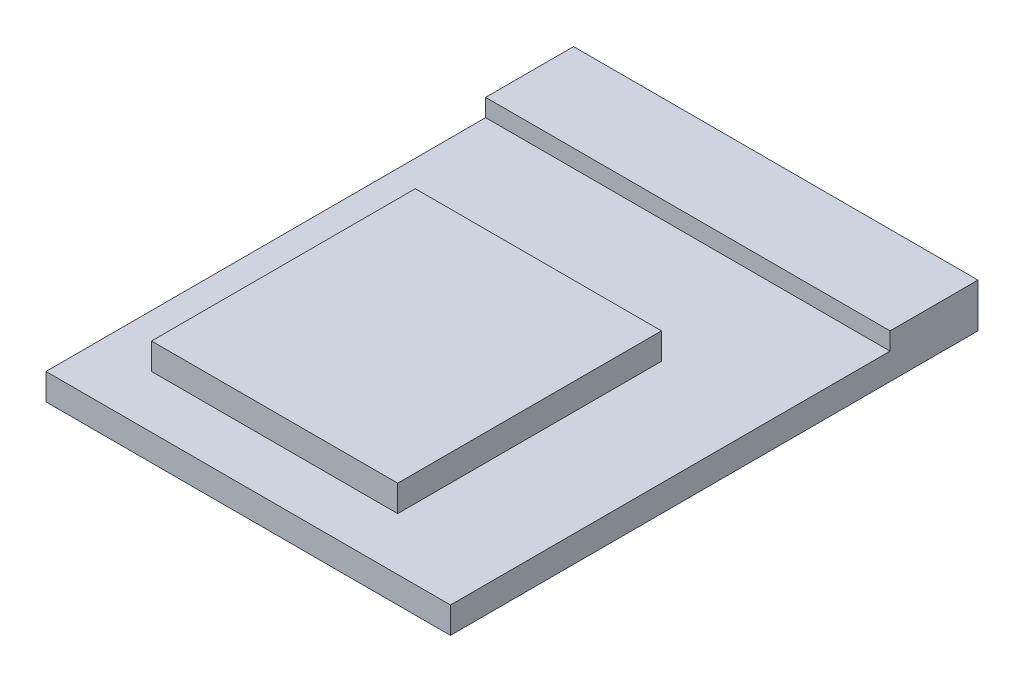
SolidWorks part; units mm, degrees
other "Исправление1"
sketch "Эскиз4"
other "Исправление2"
sketch "Эскиз5"
other "Исправление3"
sketch "Эскиз6" plane through (23, 3, 30) normal (0.5061, 0.739, 0.4446) x (0.6964, -0.0461, -0.7162)
ref_plane "Спереди" through (0, 0, 0) normal (0, 0, 1) x (1, 0, 0)
ref_plane "Сверху" through (0, 0, 0) normal (0, 1, 0) x (1, 0, 0)
ref_plane "Справа" through (0, 0, 0) normal (1, 0, 0) x (0, 0, -1)
other "Configuration Table"
sketch "Эскиз1" plane through (0, 0, 0) normal (0, 1, 0) x (1, 0, 0)
  line L1 (0, 0) -> (23, 0)
  line L2 (0, 0) -> (0, -30)
  line L3 (0, -30) -> (23, -30)
  line L4 (23, 0) -> (23, -30)
  dimension "D1" = 23
  dimension "D2" = 30
extrude "Бобышка-Вытянуть1" add sketch "Эскиз1" along normal blind 1.5
sketch "Эскиз2" plane through (0, 1.5, 0) normal (0, 1, 0) x (1, 0, 0)
  line L0 (23, -30) -> (23, 0) construction
  line L1 (3, -12) -> (17, -12)
  line L2 (3, -12) -> (3, -27)
  line L3 (3, -27) -> (17, -27)
  line L4 (17, -12) -> (17, -27)
  line L5 (0, 0) -> (0, -30) construction
  line L6 (0, -30) -> (23, -30) construction
  dimension "D1" = 6
  dimension "D2" = 3
  dimension "D3" = 15
  dimension "D4" = 3
extrude "Бобышка-Вытянуть2" add sketch "Эскиз2" along normal blind 1.5
sketch "Эскиз3" plane through (0, 1.5, 0) normal (0, 1, 0) x (1, 0, 0)
  line L0 (23, -30) -> (23, 0) construction
  line L1 (0, 0) -> (23, 0)
  line L2 (0, 0) -> (0, -5)
  line L3 (0, -5) -> (23, -5)
  line L4 (23, 0) -> (23, -5)
  dimension "D1" = 5
extrude "Бобышка-Вытянуть3" add sketch "Эскиз3" along normal blind 1 contours L2 L1 L4 L3
